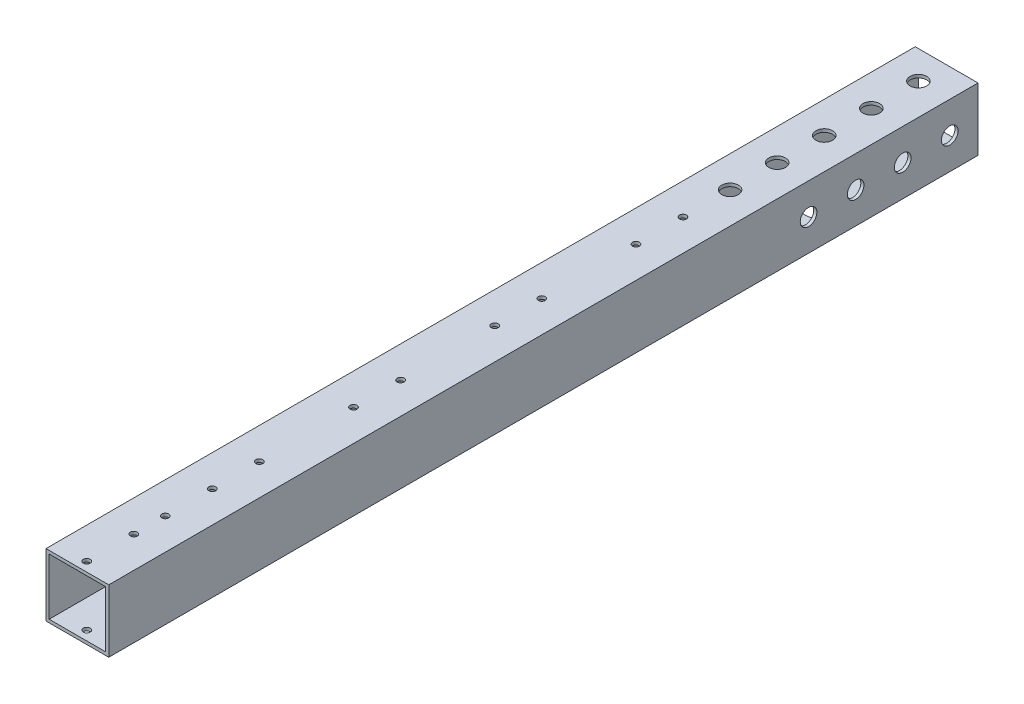
SolidWorks part; units mm, degrees
ref_plane "前视基准面" through (0, 0, 0) normal (0, 0, 1) x (1, 0, 0)
ref_plane "上视基准面" through (0, 0, 0) normal (0, 1, 0) x (1, 0, 0)
ref_plane "右视基准面" through (0, 0, 0) normal (1, 0, 0) x (0, 0, -1)
sketch "草图1" plane through (0, 0, 0) normal (0, 0, 1) x (1, 0, 0)
  line L1 (0, 0) -> (20, 0)
  line L2 (0, 0) -> (0, -20)
  line L3 (0, -20) -> (20, -20)
  line L4 (20, 0) -> (20, -20)
  line L5 (19, -19) -> (1, -19)
  line L6 (19, -19) -> (19, -1)
  line L7 (19, -1) -> (1, -1)
  line L8 (1, -19) -> (1, -1)
  dimension "D1" = 20
  dimension "D2" = 20
  dimension "D3" = 18
  dimension "D4" = 1
  dimension "D5" = 1
  dimension "D6" = 18
extrude "凸台-拉伸2" add sketch "草图1" along normal blind 277
sketch "草图2" plane through (0, -20, 0) normal (0, -1, 0) x (-1, 0, 0)
  line L0 (0, 0) -> (-20, 0) construction
  line L1 (-20, -277) -> (-20, 0) construction
  circle A0 centre (-10, -9) radius 2.65
  circle A1 centre (-10, -24) radius 2.65
  circle A2 centre (-10, -39) radius 2.65
  circle A3 centre (-10, -54) radius 2.65
  circle A4 centre (-10, -69) radius 2.65
  circle A6 centre (-10, -99) radius 1.1
  circle A8 centre (-10, -129) radius 1.1
  circle A9 centre (-10, -144) radius 1.1
  circle A11 centre (-10, -174) radius 1.1
  circle A12 centre (-10, -189) radius 1.1
  circle A14 centre (-10, -219) radius 1.1
  circle A15 centre (-10, -234) radius 1.1
  circle A16 centre (-10, -249) radius 1.1
  circle A17 centre (-10, -84) radius 2.65 [skipped]
  circle A18 centre (-10, -84) radius 1.1
  circle A19 centre (-10, -114) radius 1.1 [skipped]
  circle A20 centre (-10, -159) radius 1.1 [skipped]
  circle A21 centre (-10, -204) radius 1.1 [skipped]
  circle A22 centre (-10, -259) radius 1.1
  circle A23 centre (-10, -274) radius 1.1
  dimension "D1" = 9
  dimension "D2" = 10
  dimension "D3" = 5.3
  dimension "D5" = 2
  dimension "D8" = 2.2
  dimension "D4" = 6
  dimension "D6" = 9
  dimension "D7" = 3
extrude "切除-拉伸1" cut sketch "草图2" against normal blind 20
sketch "草图5" plane through (0, 0, 0) normal (-1, 0, 0) x (0, 0, 1)
  line L0 (277, 0) -> (0, 0) construction
  line L1 (0, 0) -> (0, -20) construction
  circle A0 centre (9, -10) radius 2.65
  circle A1 centre (24, -10) radius 2.65
  circle A2 centre (39, -10) radius 2.65
  circle A3 centre (54, -10) radius 2.65
  circle A5 centre (69, -10) radius 2.65 [skipped]
  dimension "D1" = 10
  dimension "D2" = 9
  dimension "D4" = 5.3
  dimension "D3" = 5
extrude "切除-拉伸2" cut sketch "草图5" against normal blind 20
sketch "草图6" plane through (0, -20, 0) normal (0, -1, 0) x (-1, 0, 0)
  circle A2 centre (-10, -39) radius 6
  circle A3 centre (-10, -54) radius 6
  circle A4 centre (-10, -69) radius 6
extrude "切除-拉伸3" cut sketch "草图6" against normal blind 10
